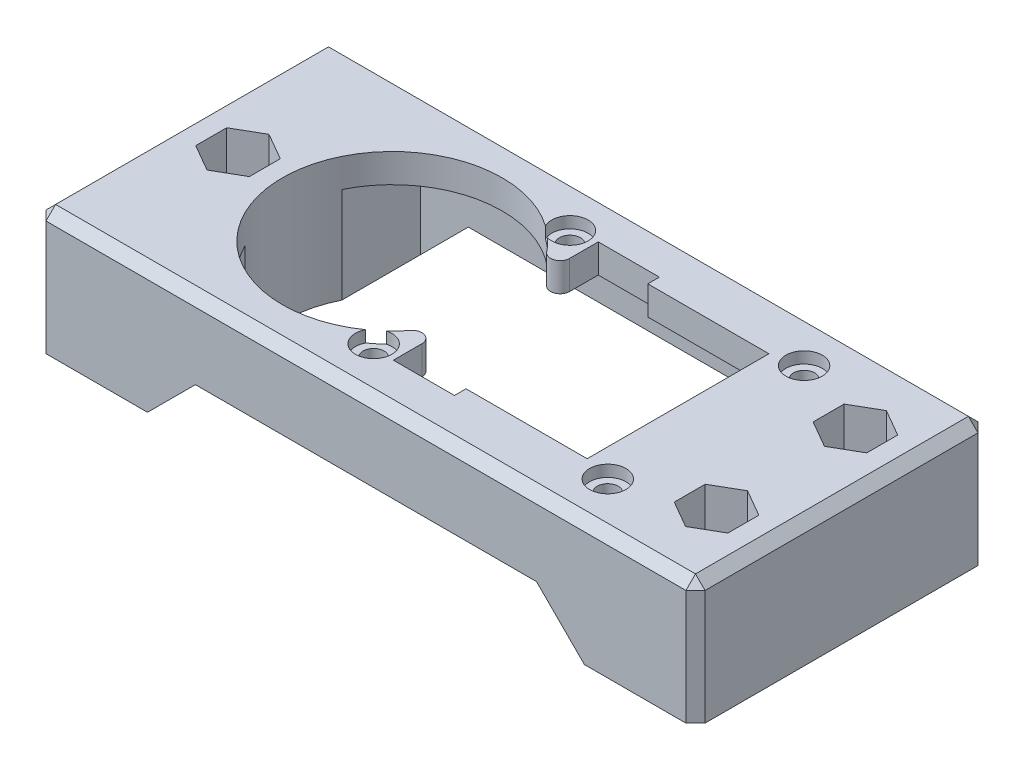
SolidWorks part; units mm, degrees
ref_plane "Plan de face" through (0, 0, 0) normal (0, 0, 1) x (1, 0, 0)
ref_plane "Plan de dessus" through (0, 0, 0) normal (0, 1, 0) x (1, 0, 0)
ref_plane "Plan de droite" through (0, 0, 0) normal (1, 0, 0) x (0, 0, -1)
sketch "Esquisse1" plane through (0, 0, 0) normal (0, 1, 0) x (1, 0, 0)
  line L0 (0, 0) -> (0, 20.5) construction
  line L1 (0, 20.5) -> (24.45, 20.5) construction
  line L2 (24.45, 20.5) -> (24.45, 0) construction
  line L3 (24.45, 0) -> (0, 0) construction
  line L8 (8.89, 19.74) -> (21.54, 19.74)
  line L9 (21.54, 19.74) -> (21.54, 0.76)
  line L10 (21.54, 0.76) -> (8.89, 0.76)
  line L12 (2.51, 20.95) -> (8.89, 20.95)
  line L13 (2.51, 20.95) -> (2.51, -0.45)
  line L14 (2.51, -0.45) -> (8.89, -0.45)
  line L15 (8.89, 20.95) -> (8.89, -0.45)
  line L22 (-21.05, 23.5) -> (-21.05, -3)
  line L24 (29.45, -3) -> (29.45, 23.5)
  line L25 (29.45, 23.5) -> (-21.05, 23.5)
  line L26 (-21.05, -3) -> (29.45, -3)
  circle A0 centre (0, 0) radius 1.1
  circle A1 centre (24.45, 0) radius 1.1
  circle A2 centre (24.45, 20.5) radius 1.1
  circle A3 centre (0, 20.5) radius 1.1
  circle A8 centre (-8.3, 10.25) radius 11.48
  point P17 (21.54, 10.25)
  point P22 (24.45, 10.25)
  point P28 (8.89, 10.25)
  point P31 (0, 10.25)
  dimension "D1" = 2.2
  dimension "D4" = 12.75
  dimension "D14" = 22.96
  dimension "D2" = 20.5
  dimension "D3" = 24.45
  dimension "D9" = 18.98
  dimension "D10" = 12.65
  dimension "D11" = 6.38
  dimension "D12" = 21.4
  dimension "D13" = 2.91
  dimension "D15" = 8.3
  dimension "D22" = 3
  dimension "D23" = 5
  dimension "D24" = 3
extrude "Boss.-Extru.1" add sketch "Esquisse1" along normal blind 3
fillet "Congé1" radius 1 2 edges at (2.51, 1.5, -14.1145) (2.51, 1.5, -6.3855)
hole_wizard "Chambrage pour vis à six pans creux M1.61" positions "Esquisse2" profile "Esquisse3" counterbore size "M1.6" standard "ISO" end condition through all
sketch "Esquisse2" plane through (0, 3, 0) normal (0, 1, 0) x (1, 0, 0)
  point P12 (0, 0)
  point P15 (0, 20.5)
  point P18 (24.45, 20.5)
  point P21 (24.45, 0)
sketch "Esquisse3" plane through (0, 3, 0) normal (1, 0, 0) x (0, 0, 1)
  line L0 (0, 0) -> (0, 3)
  line L1 (0, 3) -> (1.1, 3)
  line L3 (1.1, 3) -> (1.1, 1.2)
  line L4 (1.1, 1.2) -> (1.9, 1.2)
  line L5 (1.9, 1.2) -> (1.9, 0)
  line L7 (1.9, 0) -> (0, 0)
  line L11 (0, -6.35) -> (0, 107.95) construction
  dimension "Diamètre du perçage jusqu'au prochain" = 2.2
  dimension "Profondeur du perçage jusqu'au prochain" = 3
  dimension "Diamètre du chambrage" = 3.8
  dimension "Profondeur du chambrage" = 1.2
sketch "Esquisse4" plane through (0, 3, 0) normal (0, 1, 0) x (1, 0, 0)
  line L0 (-21.05, 23.5) -> (-21.05, -3) construction
  line L1 (-18.61, 23.5) -> (-30.21, 23.5)
  line L2 (-18.61, 23.5) -> (-18.61, 15.2992)
  line L3 (-18.61, -3) -> (-30.21, -3)
  line L4 (-30.21, 23.5) -> (-30.21, -3)
  line L5 (29.45, 23.5) -> (-21.05, 23.5) construction
  line L6 (27.01, 23.5) -> (38.61, 23.5)
  line L12 (-18.61, 15.2992) -> (-18.61, 5.2008) construction
  line L13 (-18.61, 5.2008) -> (-18.61, -3)
  line L14 (27.01, 23.5) -> (27.01, -3)
  line L16 (-30.21, 17.5) -> (-18.61, 17.5) construction
  line L17 (-30.21, 10.25) -> (-56.6243, 10.25) construction
  line L18 (4.2, 23.5) -> (4.2, 41.2903) construction
  line L19 (-21.05, -3) -> (29.45, -3) construction
  line L20 (27.01, -3) -> (38.61, -3)
  line L21 (38.61, -3) -> (38.61, 23.5)
  line L22 (29.45, -3) -> (29.45, 23.5) construction
  arc A0 (-1.6935, 19.6385) -> (-1.6935, 0.8615) centre (-8.3, 10.25) ccw construction
  arc A1 (-18.61, 15.2992) -> (-18.61, 5.2008) centre (-8.3, 10.25) ccw
  circle A2 centre (-24.41, 10.25) radius 1.6
  circle A5 centre (32.81, 3) radius 1.6
  arc A6 (-18.61, 5.2008) -> (-1.6935, 0.8615) centre (-8.3, 10.25) ccw construction
  arc A7 (-1.6935, 19.6385) -> (-18.61, 15.2992) centre (-8.3, 10.25) ccw construction
  circle A10 centre (32.81, 17.5) radius 1.6
  dimension "D5" = 6
  dimension "D8" = 3.2
  dimension "D1" = 9.16
  dimension "D2" = 11.6
  dimension "D3" = 9.16
  dimension "D4" = 11.6
  dimension "D6" = 6
  dimension "D7" = 5.8
  dimension "D9" = 6
  dimension "D10" = 5.8
extrude "Boss.-Extru.2" add sketch "Esquisse4" against normal blind 19
sketch "Esquisse5" plane through (0, -16, 0) normal (0, -1, 0) x (1, 0, 0)
  line L1 (-24.41, -7.0168) -> (-27.21, -8.6334)
  line L2 (-27.21, -8.6334) -> (-27.21, -11.8666)
  line L3 (-27.21, -11.8666) -> (-24.41, -13.4832)
  line L4 (-24.41, -13.4832) -> (-21.61, -11.8666)
  line L5 (-21.61, -11.8666) -> (-21.61, -8.6334)
  line L6 (-21.61, -8.6334) -> (-24.41, -7.0168)
  line L13 (32.81, -14.2668) -> (30.01, -15.8834)
  line L14 (30.01, -15.8834) -> (30.01, -19.1166)
  line L15 (30.01, -19.1166) -> (32.81, -20.7332)
  line L16 (32.81, -20.7332) -> (35.61, -19.1166)
  line L17 (35.61, -19.1166) -> (35.61, -15.8834)
  line L18 (35.61, -15.8834) -> (32.81, -14.2668)
  line L19 (32.81, 0.2332) -> (30.01, -1.3834)
  line L20 (30.01, -1.3834) -> (30.01, -4.6166)
  line L21 (30.01, -4.6166) -> (32.81, -6.2332)
  line L22 (32.81, -6.2332) -> (35.61, -4.6166)
  line L23 (35.61, -4.6166) -> (35.61, -1.3834)
  line L24 (35.61, -1.3834) -> (32.81, 0.2332)
  circle A0 centre (-24.41, -10.25) radius 2.8 construction
  circle A2 centre (32.81, -17.5) radius 2.8 construction
  circle A3 centre (32.81, -3) radius 2.8 construction
  dimension "D1" = 5.6
extrude "Enlèv. mat.-Extru.1" cut sketch "Esquisse5" along normal blind 7 from surface at -19 starting at face at (4.2, 3, -10.25)
sketch "Esquisse6" plane through (0, 0, -23.5) normal (0, 0, -1) x (-1, 0, 0)
  line L0 (-38.61, -16) -> (-38.61, 3) construction
  line L1 (-27.01, -16) -> (-38.61, -16)
  line L2 (-27.01, -16) -> (-27.01, -10)
  line L3 (-27.01, -10) -> (-38.61, -10)
  line L4 (-38.61, -16) -> (-38.61, -10)
  line L5 (-27.01, 0) -> (18.61, 0) construction
  line L6 (30.21, -16) -> (30.21, 3) construction
  line L7 (18.61, -16) -> (30.21, -16)
  line L8 (18.61, -16) -> (18.61, -10)
  line L9 (18.61, -10) -> (30.21, -10)
  line L10 (30.21, -16) -> (30.21, -10)
  dimension "D1" = 10
  dimension "D2" = 10
extrude "Enlèv. mat.-Extru.2" cut sketch "Esquisse6" against normal through all
ref_plane "Plan1" through (0, 0, -10.25) normal (0, 0, -1) x (-1, 0, 0)
sketch "Esquisse7" plane through (0, 0, -23.5) normal (0, 0, -1) x (-1, 0, 0)
  line L0 (-4.2, 0) -> (-4.2, 16.2892) construction
  line L3 (-27.01, -10) -> (-17.01, 0)
  line L4 (18.61, -10) -> (8.61, 0)
  line L5 (-22.01, -5) -> (13.61, -5)
  line L12 (-38.61, -10) -> (-27.01, -10)
  line L14 (-27.01, -10) -> (-27.01, 0)
  line L25 (-27.01, 0) -> (18.61, 0)
  line L26 (18.61, 0) -> (18.61, -10)
  line L28 (18.61, -10) -> (30.21, -10)
  line L29 (30.21, -10) -> (30.21, 3)
  line L30 (30.21, 3) -> (-38.61, 3)
  line L31 (-38.61, 3) -> (-38.61, -10)
  line L32 (-38.61, -10) -> (-27.01, -10)
  line L34 (-17.01, 0) -> (8.61, 0)
  line L36 (18.61, -10) -> (30.21, -10)
  line L37 (30.21, -10) -> (30.21, 3)
  line L38 (30.21, 3) -> (-38.61, 3)
  line L39 (-38.61, 3) -> (-38.61, -10)
  line M12 (-38.61, -10) -> (-27.01, -10)
  line M13 (-27.01, -10) -> (-27.01, 0)
  line M14 (-27.01, 0) -> (18.61, 0)
  line M15 (18.61, 0) -> (18.61, -10)
  line M17 (30.21, -10) -> (30.21, 3)
  line M18 (30.21, 3) -> (-38.61, 3)
  line M19 (-38.61, 3) -> (-38.61, -10)
  line M20 (18.61, -10) -> (30.21, -10)
  dimension "D2" = 10
  dimension "D1" = 0
extrude "Boss.-Extru.3" add sketch "Esquisse7" along normal blind 2 contours L3 L5 L4 L34 M14 | L3 M13 M14 | L0 L38 M14 M19 M12 M13 | L4 M15 M14 | L0 L34 M14 M15 M20 M17 M18
mirror "Symétrie1" about plane through (0, 0, -10.25) normal (0, 0, -1) of "Boss.-Extru.3"
chamfer "Chanfrein1" distance 1 angle 45 8 edges at (-30.21, 3, -10.25) (38.61, 3, -10.25) (-30.21, -3.5, -25.5) (4.2, 3, -25.5) (38.61, -3.5, -25.5) (38.61, -3.5, 5) (4.2, 3, 5) (-30.21, -3.5, 5)
